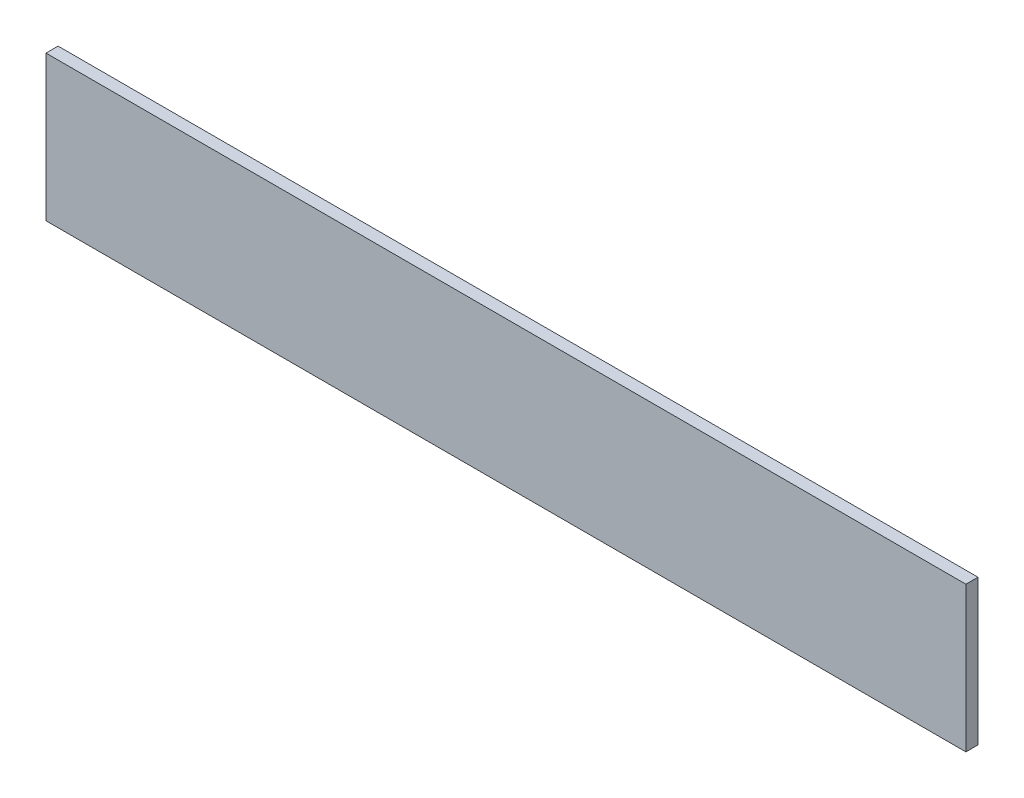
SolidWorks part; units mm, degrees
ref_plane "Front Plane" through (0, 0, 0) normal (0, 0, 1) x (1, 0, 0)
ref_plane "Top Plane" through (0, 0, 0) normal (0, 1, 0) x (1, 0, 0)
ref_plane "Right Plane" through (0, 0, 0) normal (1, 0, 0) x (0, 0, -1)
ref_plane "Plane1" through (0, 0, 24) normal (0, 0, 1) x (1, 0, 0)
sketch "Sketch1" plane through (0, 0, 24) normal (0, 0, 1) x (1, 0, 0)
  line L1 (-38, -46) -> (38, -46)
  line L2 (-38, -46) -> (-38, -34)
  line L3 (-38, -34) -> (38, -34)
  line L4 (38, -46) -> (38, -34)
  line L5 (-38, -46) -> (38, -34) construction
  line L6 (-38, -34) -> (38, -46) construction
  point P0 (0, -40)
extrude "Boss-Extrude1" add sketch "Sketch1" along normal blind 1
